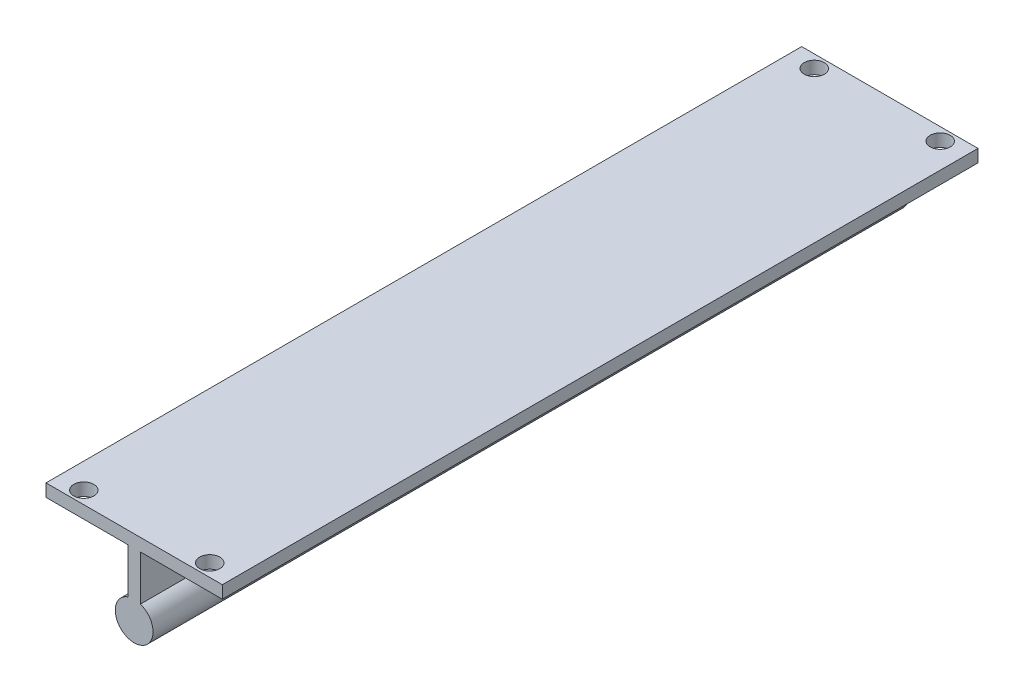
SolidWorks part; units mm, degrees
ref_plane "Front Plane" through (0, 0, 0) normal (0, 0, 1) x (1, 0, 0)
ref_plane "Top Plane" through (0, 0, 0) normal (0, 1, 0) x (1, 0, 0)
ref_plane "Right Plane" through (0, 0, 0) normal (1, 0, 0) x (0, 0, -1)
sketch "Sketch1" plane through (0, 0, 0) normal (0, 0, 1) x (1, 0, 0)
  circle A0 centre (0, 0) radius 7.5
  dimension "D1" = 15
extrude "Boss-Extrude1" add sketch "Sketch1" along normal blind 300
sketch "Sketch3" plane through (0, 0, 300) normal (0, 0, 1) x (1, 0, 0)
  line L0 (-2.5, 0) -> (2.5, 0)
  line L1 (-2.5, 0) -> (-2.5, 30)
  line L2 (-2.5, 30) -> (2.5, 30)
  line L3 (2.5, 30) -> (2.5, 0)
  point P5 (0, 0)
  dimension "D1" = 5
  dimension "D2" = 30
extrude "Boss-Extrude2" add sketch "Sketch3" against normal up to surface (300 mm away) up to face at (7.5, 0, 0)
sketch "Sketch4" plane through (0, 0, 300) normal (0, 0, 1) x (1, 0, 0)
  line L0 (0, 0) -> (0, 30) construction
  line L1 (2.5, 30) -> (-2.5, 30) construction
  line L2 (-35, 30) -> (35, 30)
  line L3 (-35, 30) -> (-35, 25)
  line L4 (-35, 25) -> (35, 25)
  line L5 (35, 25) -> (35, 30)
  dimension "D1" = 35
  dimension "D2" = 5
extrude "Boss-Extrude3" add sketch "Sketch4" against normal up to surface (300 mm away) up to face at (0, 14.8928, 0)
sketch "Sketch6" plane through (0, 30, 0) normal (0, 1, 0) x (1, 0, 0)
  line L0 (0, 0) -> (0, -300) construction
  line L1 (35, -300) -> (-35, -300) construction
  line L2 (0, 0) -> (0, -150) construction
  line L3 (0, -150) -> (35, -150) construction
  line L4 (35, 0) -> (35, -300) construction
  circle A0 centre (-25, -5) radius 4
  circle A1 centre (25, -5) radius 4
  circle A2 centre (25, -295) radius 4
  circle A3 centre (-25, -295) radius 4
  point P5 (-25, -5)
  dimension "D3" = 8
  dimension "D1" = 25
  dimension "D2" = 145
extrude "Cut-Extrude1" cut sketch "Sketch6" against normal through all both and the other way through all
